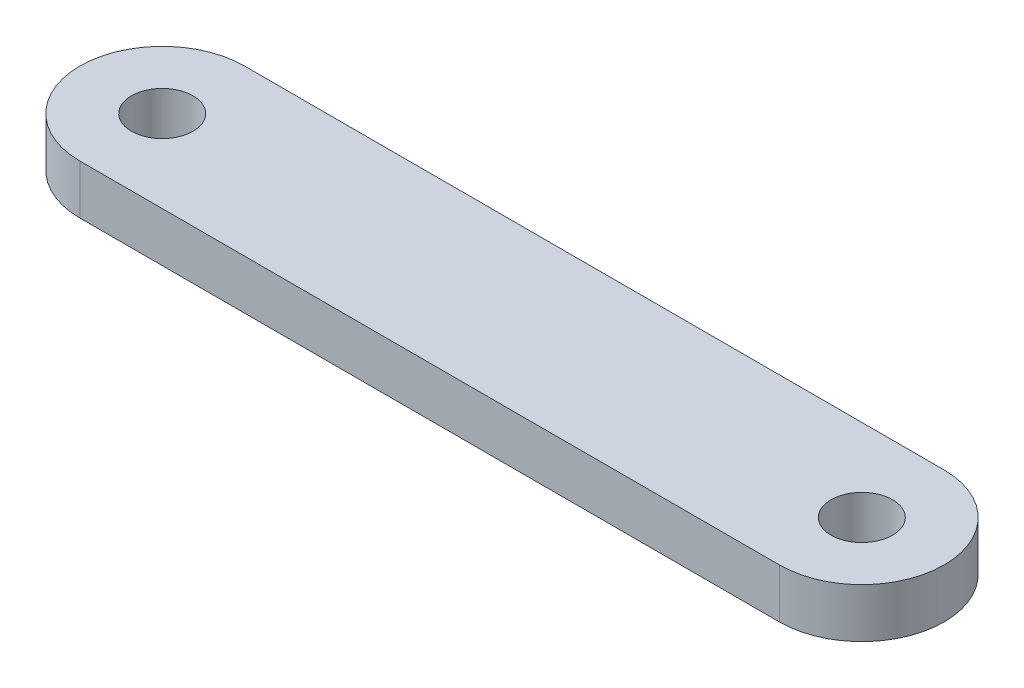
SolidWorks part; units mm, degrees
ref_plane "Plan de face" through (0, 0, 0) normal (0, 0, 1) x (1, 0, 0)
ref_plane "Plan de dessus" through (0, 0, 0) normal (0, 1, 0) x (1, 0, 0)
ref_plane "Plan de droite" through (0, 0, 0) normal (1, 0, 0) x (0, 0, -1)
sketch "Esquisse1" plane through (0, 0, 0) normal (0, 1, 0) x (1, 0, 0)
  line L0 (-21.59, 0) -> (21.59, 0) construction
  line L1 (-1.0478, 0) -> (1.0478, 0) construction
  line L2 (-21.59, 5.08) -> (21.59, 5.08)
  line L3 (-21.59, -5.08) -> (21.59, -5.08)
  arc A0 (-21.59, 5.08) -> (-21.59, -5.08) centre (-21.59, 0) ccw
  arc A1 (21.59, -5.08) -> (21.59, 5.08) centre (21.59, 0) ccw
  point P5 (0, 0)
  dimension "D1" = 5.08
  dimension "D2" = 43.18
extrude "Boss.-Extru.1" add sketch "Esquisse1" along normal blind 3.048
hole_wizard "Dégagement #61" positions "Esquisse2" profile "Esquisse3" hole size "#6" standard "Ansi Inch" end condition through all
sketch "Esquisse2" plane through (0, 3.048, 0) normal (0, 1, 0) x (1, 0, 0)
  point P0 (-21.59, 0)
  point P3 (21.59, 0)
sketch "Esquisse3" plane through (-21.59, 3.048, 0) normal (1, 0, 0) x (0, 0, 1)
  line L0 (0, 0) -> (0, 3.048)
  line L1 (0, 3.048) -> (1.8986, 3.048)
  line L2 (1.8986, 3.048) -> (1.8986, 0)
  line L5 (1.8986, 0) -> (0, 0)
  line L11 (0, -6.35) -> (0, 107.95) construction
  dimension "Diamètre du perçage jusqu'au prochain" = 3.7973
  dimension "Profondeur du perçage jusqu'au prochain" = 3.048
sketch "Esquisse4" plane through (0, 3.048, 0) normal (0, 1, 0) x (1, 0, 0)
  point P0 (-21.59, 0)
  point P1 (21.59, 0)
